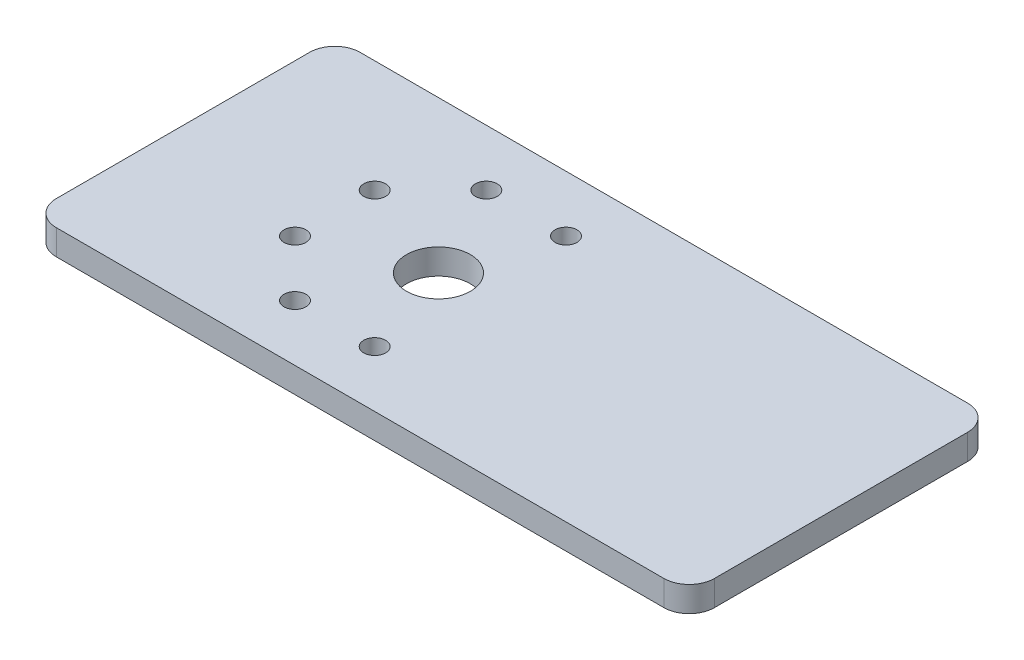
SolidWorks part; units mm, degrees
ref_plane "Front Plane" through (0, 0, 0) normal (0, 0, 1) x (1, 0, 0)
ref_plane "Top Plane" through (0, 0, 0) normal (0, 1, 0) x (1, 0, 0)
ref_plane "Right Plane" through (0, 0, 0) normal (1, 0, 0) x (0, 0, -1)
sketch "Sketch1" plane through (0, 0, 0) normal (0, 1, 0) x (1, 0, 0)
  line L1 (-82.55, 38.1) -> (82.55, 38.1)
  line L2 (-82.55, 38.1) -> (-82.55, -38.1)
  line L3 (-82.55, -38.1) -> (82.55, -38.1)
  line L4 (82.55, 38.1) -> (82.55, -38.1)
  line L5 (-82.55, 38.1) -> (82.55, -38.1) construction
  line L6 (-82.55, -38.1) -> (82.55, 38.1) construction
  point P0 (0, 0)
  dimension "D1" = 165.1
  dimension "D2" = 76.2
extrude "Boss-Extrude1" add sketch "Sketch1" along normal blind 6.35
hole_wizard "M5 Clearance Hole1" positions "Sketch2" profile "Sketch3" hole size "M5" standard "ANSI Metric"
sketch "Sketch2" plane through (0, 6.35, 0) normal (0, 1, 0) x (1, 0, 0)
  line L0 (-82.55, 38.1) -> (-82.55, -38.1) construction
  point P0 (-44.45, 10)
  point P3 (-44.45, -10)
  point P8 (-82.55, 0)
  point P16 (-18.45, 0)
  point P20 (-10.45, 24)
  point P22 (-10.45, -24)
  point P26 (-30.45, 24)
  point P28 (-30.45, -24)
  point P31 (0, 0)
  point P32 (0, 0)
  point P33 (0, 0)
  point P34 (0, 0)
  dimension "D1" = 10
  dimension "D2" = 20
  dimension "D3" = 38.1
  dimension "D4" = 26
  dimension "D5" = 8
  dimension "D6" = 24
  dimension "D7" = 48
  dimension "D8" = 20
sketch "Sketch3" plane through (-44.45, 6.35, -10) normal (1, 0, 0) x (0, 0, 1)
  line L0 (0, 0) -> (0, 14.3524)
  line L1 (0, 14.3524) -> (2.75, 12.7)
  line L2 (2.75, 12.7) -> (2.75, 0)
  line L5 (2.75, 0) -> (0, 0)
  line L10 (0, 14.3524) -> (-2.75, 12.7) construction
  line L11 (0, -6.35) -> (0, 107.95) construction
  dimension "Hole Dia." = 5.5
  dimension "Hole Depth" = 12.7
  dimension "Drill Angle" = 118
sketch "Sketch5" plane through (0, 6.35, 0) normal (0, 1, 0) x (1, 0, 0)
  circle A0 centre (-18.45, 0) radius 8
  dimension "D1" = 16
extrude "Cut-Extrude1" cut sketch "Sketch5" against normal blind 6.35
fillet "Fillet1" radius 6.35 4 edges at (-82.55, 3.175, -38.1) (82.55, 3.175, -38.1) (82.55, 3.175, 38.1) (-82.55, 3.175, 38.1)
